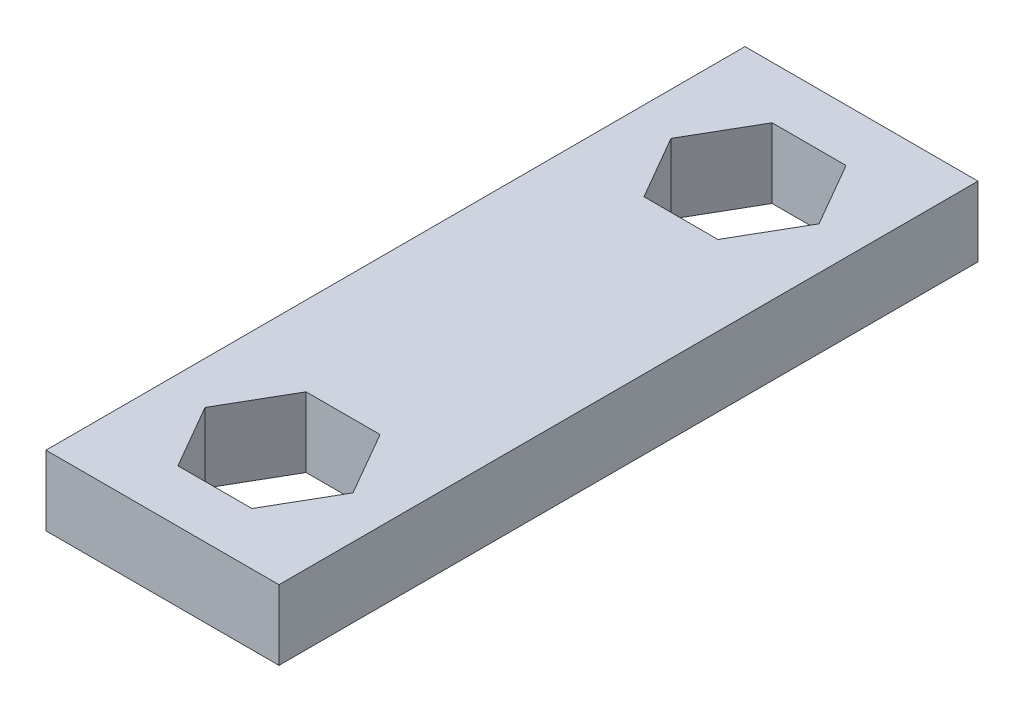
SolidWorks part; units mm, degrees
ref_plane "Front Plane" through (0, 0, 0) normal (0, 0, 1) x (1, 0, 0)
ref_plane "Top Plane" through (0, 0, 0) normal (0, 1, 0) x (1, 0, 0)
ref_plane "Right Plane" through (0, 0, 0) normal (1, 0, 0) x (0, 0, -1)
sketch "Sketch1" plane through (0, 0, 0) normal (0, 1, 0) x (1, 0, 0)
  line L0 (-1000, 15) -> (49000, 15) construction
  line L1 (0, 0) -> (10, 0)
  line L2 (0, 0) -> (0, 30)
  line L3 (0, 30) -> (10, 30)
  line L4 (10, 0) -> (10, 30)
  line L5 (1.8246, 5) -> (3.4123, 7.75)
  line L6 (3.4123, 22.25) -> (6.5877, 22.25)
  line L7 (6.5877, 22.25) -> (8.1754, 25)
  line L8 (8.1754, 25) -> (6.5877, 27.75)
  line L9 (6.5877, 27.75) -> (3.4123, 27.75)
  line L10 (3.4123, 27.75) -> (1.8246, 25)
  line L11 (1.8246, 25) -> (3.4123, 22.25)
  line L12 (3.4123, 2.25) -> (1.8246, 5)
  line L13 (6.5877, 2.25) -> (3.4123, 2.25)
  line L14 (8.1754, 5) -> (6.5877, 2.25)
  line L15 (6.5877, 7.75) -> (8.1754, 5)
  line L16 (3.4123, 7.75) -> (6.5877, 7.75)
  circle A0 centre (5, 25) radius 1.65
  circle A1 centre (5, 5) radius 1.65
  circle A2 centre (5, 25) radius 2.75 construction
  point P10 (0, 15)
  point P13 (5, 30)
  dimension "D4" = 3.3
  dimension "D1" = 10
  dimension "D2" = 30
  dimension "D3" = 5
  dimension "D5" = 5.5
extrude "Boss-Extrude1" add sketch "Sketch1" along normal blind 3 contours L1 L4 L3 L2 L11 L10 L9 L8 L7 L6 L5 L16 L15 L14 L13 L12
